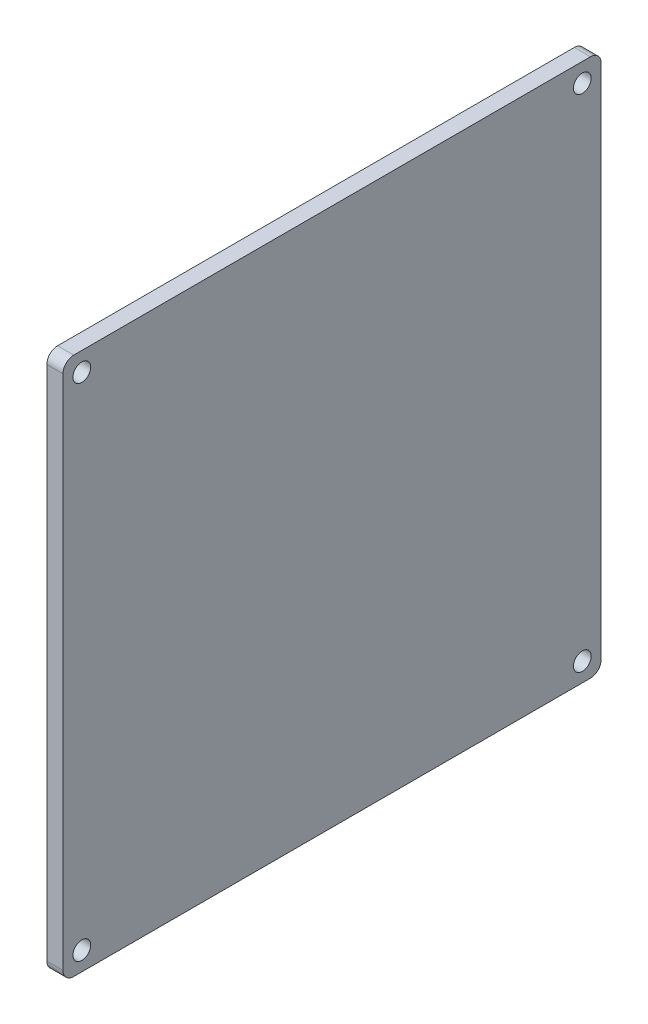
SolidWorks part; units mm, degrees
ref_plane "前视基准面" through (0, 0, 0) normal (0, 0, 1) x (1, 0, 0)
ref_plane "上视基准面" through (0, 0, 0) normal (0, 1, 0) x (1, 0, 0)
ref_plane "右视基准面" through (0, 0, 0) normal (1, 0, 0) x (0, 0, -1)
sketch "草图1" plane through (0, 0, 0) normal (1, 0, 0) x (0, 0, -1)
  line L1 (0, 0) -> (100, 0)
  line L2 (0, 0) -> (0, -100)
  line L3 (0, -100) -> (100, -100)
  line L4 (100, 0) -> (100, -100)
  dimension "D1" = 100
  dimension "D2" = 100
extrude "凸台-拉伸1" add sketch "草图1" along normal blind 3
sketch "草图2" plane through (3, 0, 0) normal (1, 0, 0) x (0, 0, -1)
  line L0 (50, 6.2064) -> (50, -104.8106) construction
  line L1 (-9.0473, -50) -> (123.0002, -50) construction
  circle A0 centre (3.5, -3.5) radius 1.65
  circle A1 centre (96.5, -3.5) radius 1.65
  circle A2 centre (96.5, -96.5) radius 1.65
  circle A3 centre (3.5, -96.5) radius 1.65
  dimension "D1" = 3.3
  dimension "D2" = 46.5
  dimension "D3" = 46.5
extrude "切除-拉伸1" cut sketch "草图2" against normal blind 3
fillet "圆角1" radius 2 1 edges at (1.5, 0, -100)
fillet "圆角2" radius 2 3 edges at (1.5, 0, 0) (1.5, -100, 0) (1.5, -100, -100)
